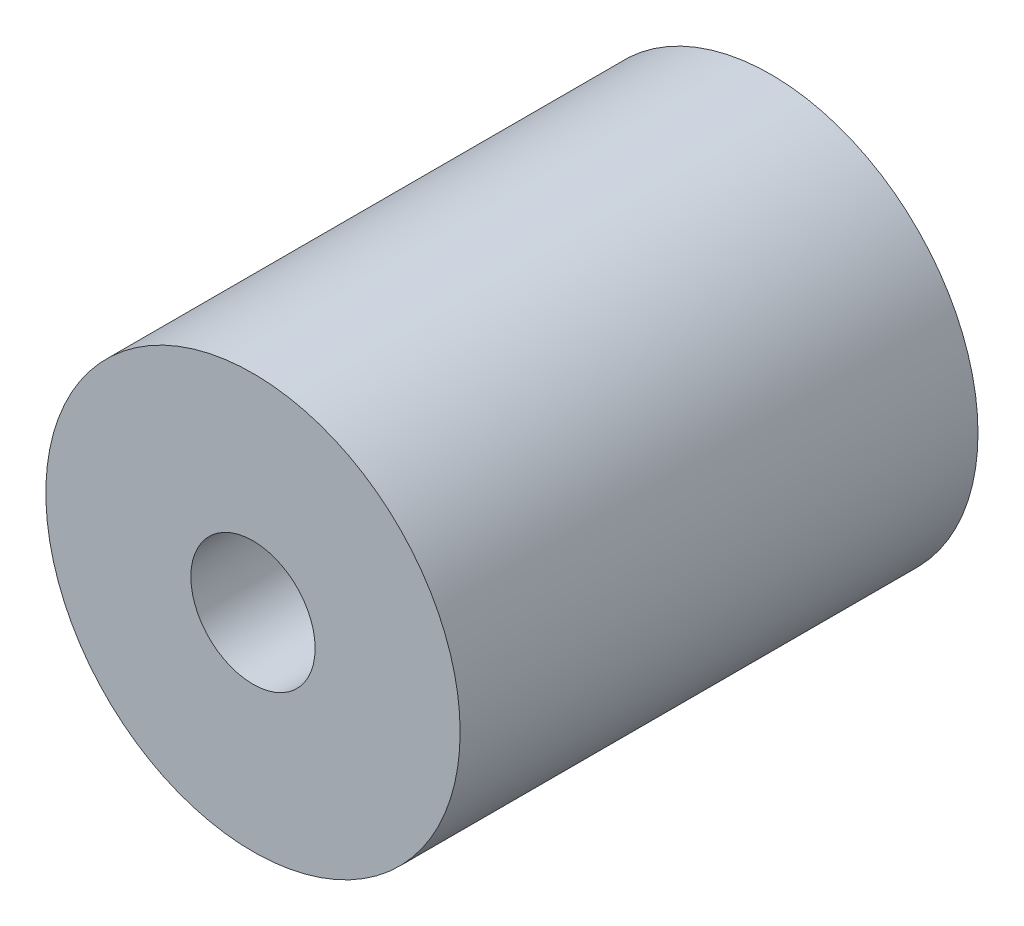
SolidWorks part; units mm, degrees
ref_plane "前视基准面" through (0, 0, 0) normal (0, 0, 1) x (1, 0, 0)
ref_plane "上视基准面" through (0, 0, 0) normal (0, 1, 0) x (1, 0, 0)
ref_plane "右视基准面" through (0, 0, 0) normal (1, 0, 0) x (0, 0, -1)
other "Configuration Table"
sketch "草图1" plane through (0, 0, 0) normal (0, 0, 1) x (1, 0, 0)
  circle A0 centre (0, 0) radius 10
  circle A1 centre (0, 0) radius 3
  dimension "D1" = 20
  dimension "D2" = 6
extrude "凸台-拉伸1" add sketch "草图1" along normal blind 25
ref_plane "基准面1" through (0, 0, 0) normal (0, 0, -1) x (-1, 0, 0)
sketch "草图2" plane through (0, 0, 0) normal (0, 0, -1) x (-1, 0, 0)
  circle A0 centre (0, 0) radius 4
extrude "切除-拉伸1" cut sketch "草图2" against normal blind 10
